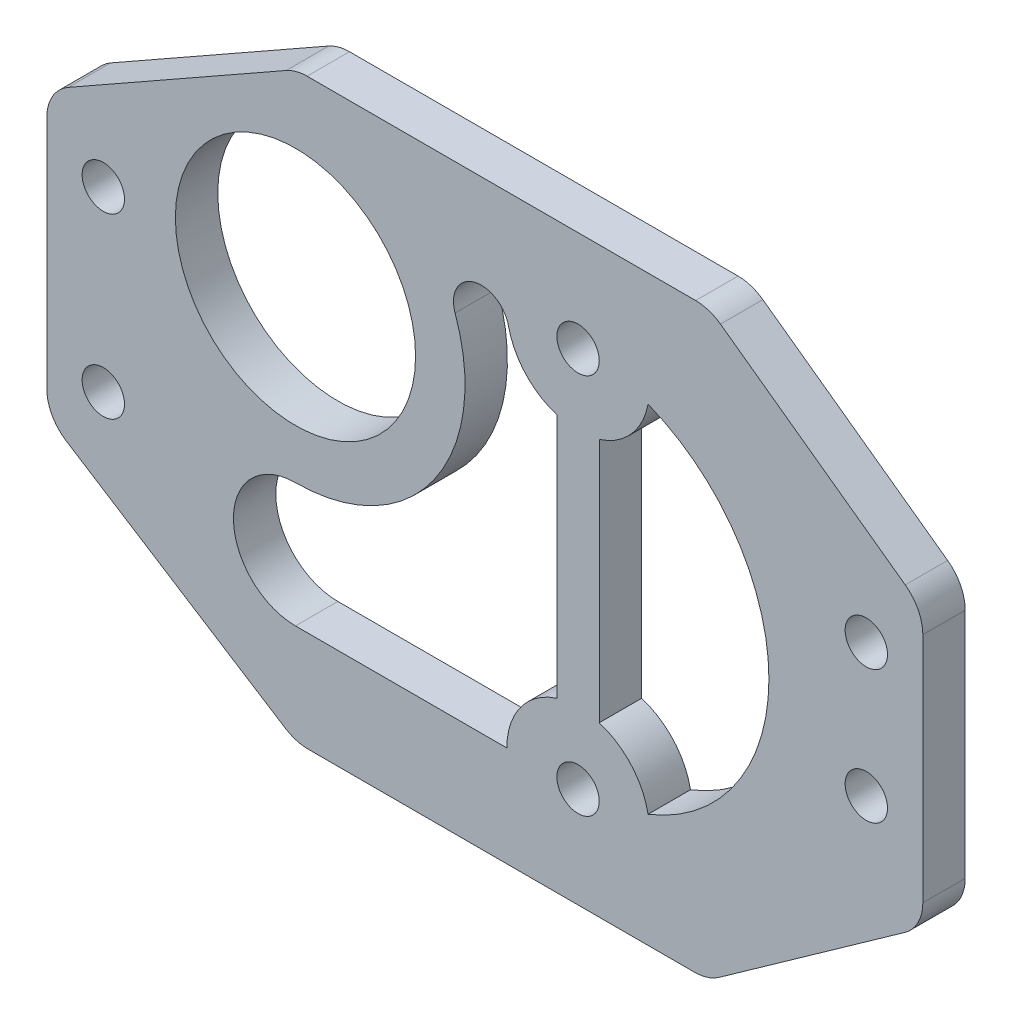
SolidWorks part; units mm, degrees
ref_plane "Front Plane" through (0, 0, 0) normal (0, 0, 1) x (1, 0, 0)
ref_plane "Top Plane" through (0, 0, 0) normal (0, 1, 0) x (1, 0, 0)
ref_plane "Right Plane" through (0, 0, 0) normal (1, 0, 0) x (0, 0, -1)
sketch "Sketch1" plane through (0, 0, 0) normal (0, 0, 1) x (1, 0, 0)
  line L0 (0, 1.648) -> (0, 18.258)
  line L1 (1.52, 20.8675) -> (16.9423, 29.6143)
  line L2 (18.4223, 30.0048) -> (45.9223, 30.0048)
  line L3 (47.6787, 29.4368) -> (60.7565, 19.9918)
  line L4 (62, 17.5597) -> (62, 1.1297)
  line L5 (60.736, -1.317) -> (47.5794, -10.6519)
  line L6 (45.8434, -11.2052) -> (18.5034, -11.2052)
  line L7 (16.8942, -10.7371) -> (1.3908, -0.8839)
  line L8 (1.3029, 16.0075) -> (6.6971, 16.0075) construction
  line L9 (0.2452, 3.4375) -> (7.7548, 3.4375) construction
  line L10 (17.6, 31.521) -> (17.6, -5.7675) construction
  line L11 (7.7548, 16.6798) -> (25.5136, 16.6798) construction
  line L12 (-39.3225, 9.3998) -> (106.4512, 9.3998) construction
  line L13 (39.1, 0.714) -> (39.1, 18.0856)
  line L14 (36.1, 18.0856) -> (36.1, 0.714)
  line L15 (37.6, 44.2333) -> (37.6, -14.3158) construction
  line L16 (32.5576, -4.1002) -> (17.6, -4.1002)
  arc A0 (18.5034, -11.2052) -> (16.8942, -10.7371) centre (18.5034, -8.2052) cw
  arc A1 (47.5794, -10.6519) -> (45.8434, -11.2052) centre (45.8434, -8.2052) cw
  arc A2 (60.7565, 19.9918) -> (62, 17.5597) centre (59, 17.5597) cw
  arc A3 (62, 1.1297) -> (60.736, -1.317) centre (59, 1.1297) cw
  arc A4 (45.9223, 30.0048) -> (47.6787, 29.4368) centre (45.9223, 27.0048) cw
  arc A5 (16.9423, 29.6143) -> (18.4223, 30.0048) centre (18.4223, 27.0048) cw
  arc A6 (0, 18.258) -> (1.52, 20.8675) centre (3, 18.258) cw
  arc A7 (0, 1.648) -> (1.3908, -0.8839) centre (3, 1.648) ccw
  circle A8 centre (4, 16.0075) radius 1.5
  circle A9 centre (4, 3.4375) radius 1.5
  circle A10 centre (58, 15.0918) radius 1.5
  circle A11 centre (58, 5.6783) radius 1.5
  circle A12 centre (37.6, 22.8998) radius 1.5
  circle A13 centre (37.6, -4.1002) radius 1.5
  circle A14 centre (17.6, 16.6798) radius 8.5
  arc A15 (36.1, 0.714) -> (32.5576, -4.1002) centre (37.6, -4.1002) ccw
  arc A16 (39.1, 18.0856) -> (42.5552, 21.966) centre (37.6, 22.8998) ccw
  arc A18 (32.6759, 21.814) -> (36.1, 18.0856) centre (37.6, 22.8998) ccw
  arc A19 (42.5552, -3.1664) -> (42.5552, 21.966) centre (37.6, 9.3998) ccw
  arc A20 (42.5552, -3.1664) -> (39.1, 0.714) centre (37.6, -4.1002) ccw
  arc A21 (17.6, 4.6798) -> (17.6, -4.1002) centre (17.6, 0.2898) ccw
  arc A22 (17.6, 4.6798) -> (28.8974, 20.7256) centre (17.6, 16.6798) ccw
  arc A23 (32.6759, 21.814) -> (28.8974, 20.7256) centre (30.7521, 21.3898) ccw
  point P15 (17.6307, -11.2052)
  point P18 (46.7996, -11.2052)
  point P21 (62, 19.0936)
  point P24 (62, -0.4201)
  point P27 (46.8923, 30.0048)
  point P30 (17.6307, 30.0048)
  point P33 (0, 20.0054)
  point P36 (0, 0)
  dimension "D8" = 3
  dimension "D9" = 3
  dimension "D10" = 3
  dimension "D11" = 3
  dimension "D12" = 3
  dimension "D13" = 3
  dimension "D14" = 3
  dimension "D16" = 3
  dimension "D27" = 17
  dimension "D30" = 4.71
  dimension "D31" = 24
  dimension "D32" = 3.94
  dimension "D1" = 209.56
  dimension "D2" = 41.21
  dimension "D3" = 62
  dimension "D4" = 27.34
  dimension "D5" = 27.5
  dimension "D6" = 17.73
  dimension "D7" = 16.61
  dimension "D15" = 16.43
  dimension "D17" = 4
  dimension "D18" = 4.86
  dimension "D19" = 4.9
  dimension "D20" = 4
  dimension "D21" = 20.4
  dimension "D22" = 27
  dimension "D23" = 7.105
  dimension "D24" = 17.6
  dimension "D25" = 20.605
  dimension "D26" = 7.28
  dimension "D29" = 3
other "AlignGroup1"
extrude "Boss-Extrude1" add sketch "Sketch1" along normal blind 3
